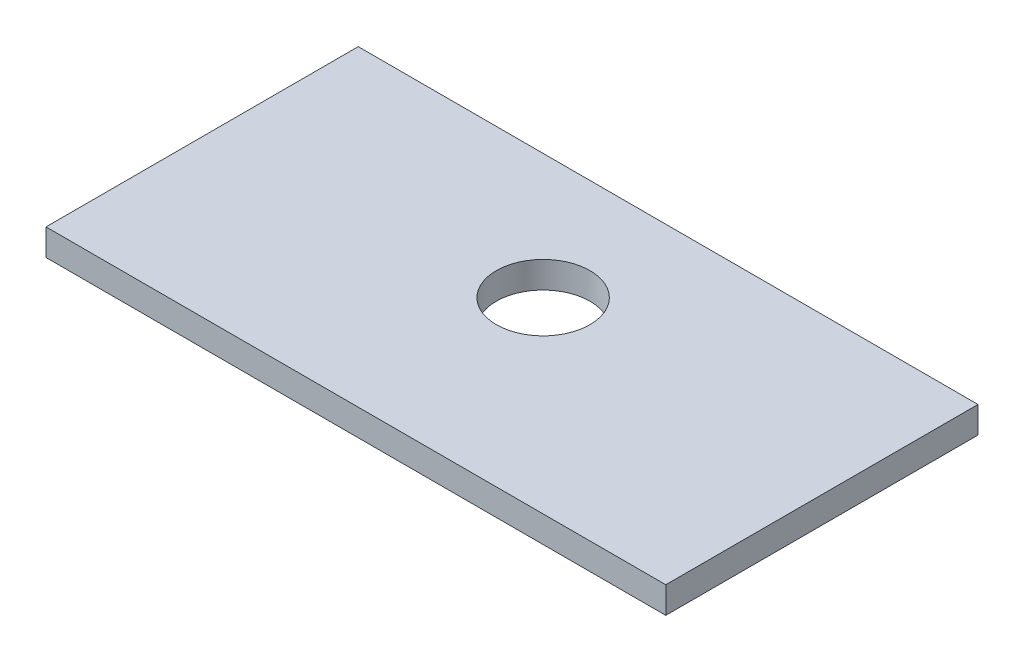
SolidWorks part; units mm, degrees
ref_plane "Front Plane" through (0, 0, 0) normal (0, 0, 1) x (1, 0, 0)
ref_plane "Top Plane" through (0, 0, 0) normal (0, 1, 0) x (1, 0, 0)
ref_plane "Right Plane" through (0, 0, 0) normal (1, 0, 0) x (0, 0, -1)
sketch "Sketch1" plane through (0, 0, 0) normal (0, 0, 1) x (1, 0, 0)
  line L1 (-54.4858, 43.4769) -> (44.7642, 43.4769)
  line L2 (-54.4858, 43.4769) -> (-54.4858, 39.2269)
  line L3 (-54.4858, 39.2269) -> (44.7642, 39.2269)
  line L4 (44.7642, 43.4769) -> (44.7642, 39.2269)
  dimension "D1" = 99.25
  dimension "D2" = 4.25
extrude "Boss-Extrude1" add sketch "Sketch1" against normal mid plane 50
sketch "Sketch2" plane through (0, 0, 0) normal (0, 1, 0) x (1, 0, 0)
  circle A0 centre (-4.8693, 4.996) radius 7.5
  dimension "D1" = 15
extrude "Cut-Extrude1" cut sketch "Sketch2" against normal blind 6 from surface at 43.4769 starting at face at (-4.8608, 43.4769, 0)
